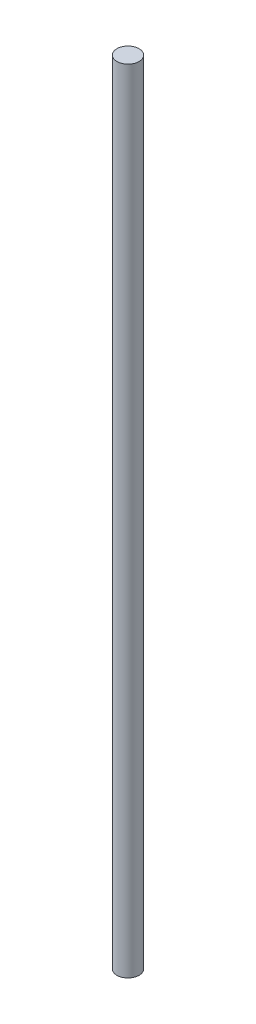
SolidWorks part; units mm, degrees
ref_plane "Front Plane" through (0, 0, 0) normal (0, 0, 1) x (1, 0, 0)
ref_plane "Top Plane" through (0, 0, 0) normal (0, 1, 0) x (1, 0, 0)
ref_plane "Right Plane" through (0, 0, 0) normal (1, 0, 0) x (0, 0, -1)
sketch "Sketch1" plane through (0, 0, 0) normal (0, 1, 0) x (1, 0, 0)
  circle A0 centre (0, 0) radius 4
  dimension "D1" = 8
extrude "Boss-Extrude1" add sketch "Sketch1" along normal blind 285
